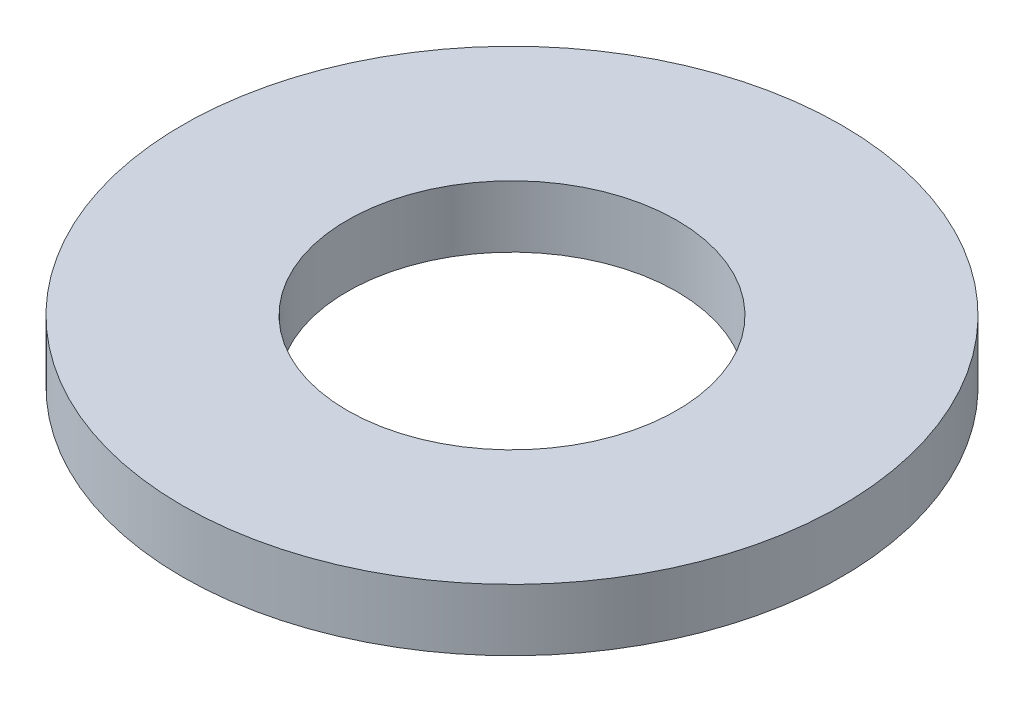
SolidWorks part; units mm, degrees
ref_plane "Front Plane" through (0, 0, 0) normal (0, 0, 1) x (1, 0, 0)
ref_plane "Top Plane" through (0, 0, 0) normal (0, 1, 0) x (1, 0, 0)
ref_plane "Right Plane" through (0, 0, 0) normal (1, 0, 0) x (0, 0, -1)
sketch "Sketch1" plane through (0, 0, 0) normal (0, 1, 0) x (1, 0, 0)
  circle A0 centre (0, 0) radius 16
  circle A1 centre (0, 0) radius 8
  dimension "D1" = 16
  dimension "D2" = 32
extrude "Boss-Extrude1" add sketch "Sketch1" along normal mid plane 3
